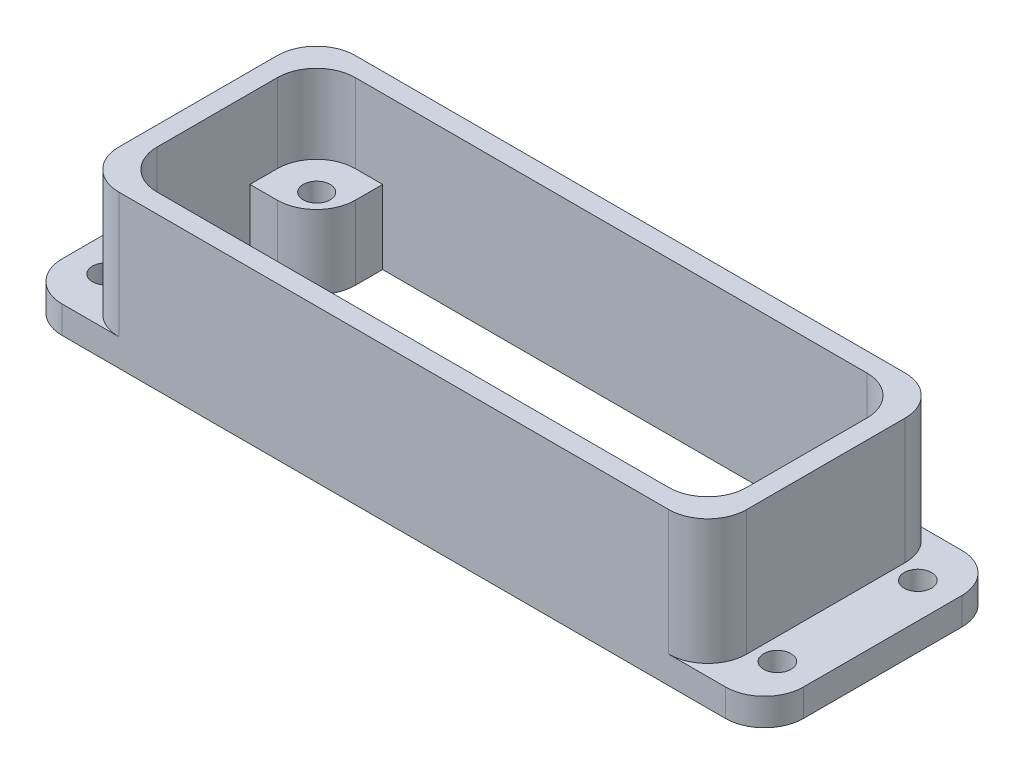
SolidWorks part; units mm, degrees
ref_plane "Спереди" through (0, 0, 0) normal (0, 0, 1) x (1, 0, 0)
ref_plane "Сверху" through (0, 0, 0) normal (0, 1, 0) x (1, 0, 0)
ref_plane "Справа" through (0, 0, 0) normal (1, 0, 0) x (0, 0, -1)
other "Configuration Table"
sketch "Эскиз1" plane through (0, 0, 0) normal (0, 1, 0) x (1, 0, 0)
  line L1 (-47.5, 15.15) -> (47.5, 15.15)
  line L2 (-47.5, 15.15) -> (-47.5, -15.15)
  line L3 (-47.5, -15.15) -> (47.5, -15.15)
  line L4 (47.5, 15.15) -> (47.5, -15.15)
  line L5 (-47.5, 15.15) -> (47.5, -15.15) construction
  line L6 (-47.5, -15.15) -> (47.5, 15.15) construction
  point P0 (0, 0)
  dimension "D1" = 95
  dimension "D2" = 30.3
extrude "Бобышка-Вытянуть1" add sketch "Эскиз1" along normal blind 3.5
sketch "Эскиз2" plane through (0, 3.5, 0) normal (0, 1, 0) x (1, 0, 0)
  line L0 (47.5, -15.15) -> (47.5, 15.15) construction
  line L1 (-40.225, 15.15) -> (40.225, 15.15)
  line L2 (-40.225, 15.15) -> (-40.225, -15.15)
  line L3 (-40.225, -15.15) -> (40.225, -15.15)
  line L4 (40.225, 15.15) -> (40.225, -15.15)
  line L5 (-40.225, 15.15) -> (40.225, -15.15) construction
  line L6 (-40.225, -15.15) -> (40.225, 15.15) construction
  point P0 (0, 0)
  dimension "D1" = 80.45
extrude "Бобышка-Вытянуть2" add sketch "Эскиз2" along normal blind 16.05
fillet "Скругление1" radius 5 8 edges at (-47.5, 1.75, 15.15) (-40.225, 11.525, 15.15) (-47.5, 1.75, -15.15) (-40.225, 11.525, -15.15) (40.225, 11.525, -15.15) (47.5, 1.75, -15.15) (40.225, 11.525, 15.15) (47.5, 1.75, 15.15)
sketch "Эскиз3" plane through (0, 19.55, 0) normal (0, 1, 0) x (1, 0, 0)
  line L0 (-40.225, 10.15) -> (-40.225, -10.15) construction
  line L1 (-32.775, 12.7) -> (32.775, 12.7)
  line L2 (-37.775, 7.7) -> (-37.775, -7.7)
  line L3 (-32.775, -12.7) -> (32.775, -12.7)
  line L4 (37.775, 7.7) -> (37.775, -7.7)
  line L5 (-37.775, 12.7) -> (37.775, -12.7) construction
  line L6 (-37.775, -12.7) -> (37.775, 12.7) construction
  line L7 (35.225, 15.15) -> (-35.225, 15.15) construction
  arc A0 (32.775, 12.7) -> (37.775, 7.7) centre (32.775, 7.7) cw
  arc A1 (37.775, -7.7) -> (32.775, -12.7) centre (32.775, -7.7) cw
  arc A2 (-32.775, -12.7) -> (-37.775, -7.7) centre (-32.775, -7.7) cw
  arc A3 (-32.775, 12.7) -> (-37.775, 7.7) centre (-32.775, 7.7) ccw
  point P0 (0, 0)
  dimension "D3" = 5
  dimension "D1" = 2.45
  dimension "D2" = 2.45
extrude "Вырез-Вытянуть1" cut sketch "Эскиз3" against normal through all both and the other way through all
sketch "Эскиз4" plane through (0, 3.5, 0) normal (0, 1, 0) x (1, 0, 0)
  line L0 (0, 15.15) -> (0, -15.15) construction
  line L1 (35.225, 15.15) -> (-35.225, 15.15) construction
  line L2 (-35.225, -15.15) -> (35.225, -15.15) construction
  line L3 (-47.5, 0) -> (47.5, 0) construction
  line L4 (-47.5, 10.15) -> (-47.5, -10.15) construction
  line L5 (47.5, -10.15) -> (47.5, 10.15) construction
  circle A0 centre (-43, 9) radius 1.75
  circle A1 centre (43, 9) radius 1.75
  circle A2 centre (-43, -9) radius 1.75
  circle A3 centre (43, -9) radius 1.75
  dimension "D1" = 3.5
  dimension "D2" = 86
  dimension "D3" = 18
extrude "Вырез-Вытянуть2" cut sketch "Эскиз4" against normal through all both and the other way through all
sketch "Эскиз5" plane through (0, 0, 0) normal (0, -1, 0) x (1, 0, 0)
  line L0 (-32.775, 12.7) -> (32.775, 12.7) construction
  line L1 (-37.775, 7.7) -> (-37.775, 4.2)
  line L2 (-37.775, -7.7) -> (-37.775, 7.7) construction
  line L4 (-32.775, 12.7) -> (-29.275, 12.7)
  line L5 (-37.775, 4.2) -> (-34.275, 4.2)
  line L7 (-29.275, 9.2) -> (-29.275, 12.7)
  line L8 (-36.3105, 11.2355) -> (-32.6411, 7.617) construction
  arc A0 (-37.775, 7.7) -> (-32.775, 12.7) centre (-32.775, 7.7) cw
  arc A2 (-37.775, 7.7) -> (-32.775, 12.7) centre (-32.775, 7.7) cw
  arc A5 (-29.275, 9.2) -> (-34.275, 4.2) centre (-34.275, 9.2) cw
  circle A6 centre (-32.6411, 7.617) radius 1.725
  dimension "D1" = 5
  dimension "D2" = 3.5
  dimension "D3" = 3.45
  dimension "D4" = 1
extrude "Бобышка-Вытянуть3" add sketch "Эскиз5" against normal offset from surface (9.45 mm away) 10.1
cosmetic thread "Условное изображение резьбы1" parameters "D2"=5
mirror "Зеркальное отражение1" about plane through (0, 0, 0) normal (0, 0, 1) of "Бобышка-Вытянуть3"
mirror "Зеркальное отражение2" about plane through (0, 0, 0) normal (1, 0, 0) of "Зеркальное отражение1", "Бобышка-Вытянуть3"
equation "\"D2@Эскиз3\"=\"D1@Эскиз3\""
